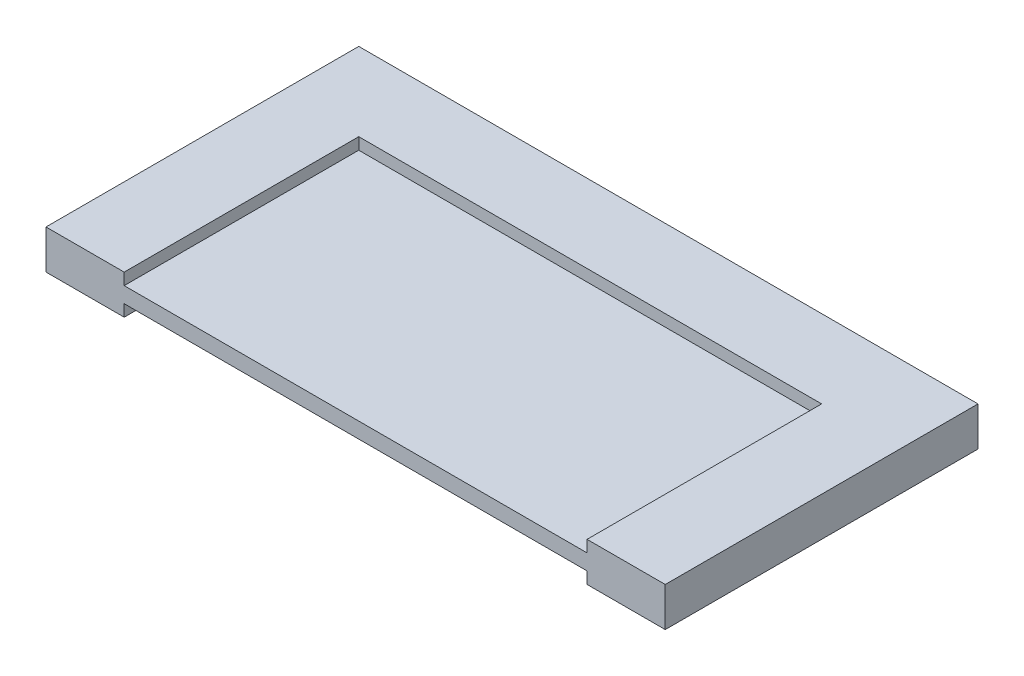
SolidWorks part; units mm, degrees
ref_plane "Front Plane" through (0, 0, 0) normal (0, 0, 1) x (1, 0, 0)
ref_plane "Top Plane" through (0, 0, 0) normal (0, 1, 0) x (1, 0, 0)
ref_plane "Right Plane" through (0, 0, 0) normal (1, 0, 0) x (0, 0, -1)
sketch "Sketch1" plane through (0, 0, 0) normal (0, 1, 0) x (1, 0, 0)
  line L0 (-25.146, 0) -> (-18.796, 0)
  line L1 (-18.796, 0) -> (-18.796, 19.05)
  line L2 (-18.796, 19.05) -> (18.796, 19.05)
  line L3 (0, 19.05) -> (0, 25.4) construction
  line L4 (25.146, 25.4) -> (-25.146, 25.4)
  line L5 (-25.146, 25.4) -> (-25.146, 0)
  line L6 (25.146, 25.4) -> (25.146, 0)
  line L7 (18.796, 0) -> (18.796, 19.05)
  line L8 (25.146, 0) -> (18.796, 0)
  dimension "D1" = 25.146
  dimension "D2" = 6.35
  dimension "D3" = 25.4
extrude "Boss-Extrude1" add sketch "Sketch1" along normal mid plane 3.175
sketch "Sketch2" plane through (0, 0, 0) normal (0, 1, 0) x (1, 0, 0)
  line L0 (18.796, 0) -> (25.146, 0) construction
  line L1 (-18.796, 19.05) -> (18.796, 19.05)
  line L2 (-18.796, 19.05) -> (-18.796, 0)
  line L3 (-18.796, 0) -> (18.796, 0)
  line L4 (18.796, 19.05) -> (18.796, 0)
  line L5 (18.796, 19.05) -> (18.796, 0) construction
extrude "Boss-Extrude2" add sketch "Sketch2" along normal mid plane 1.27
